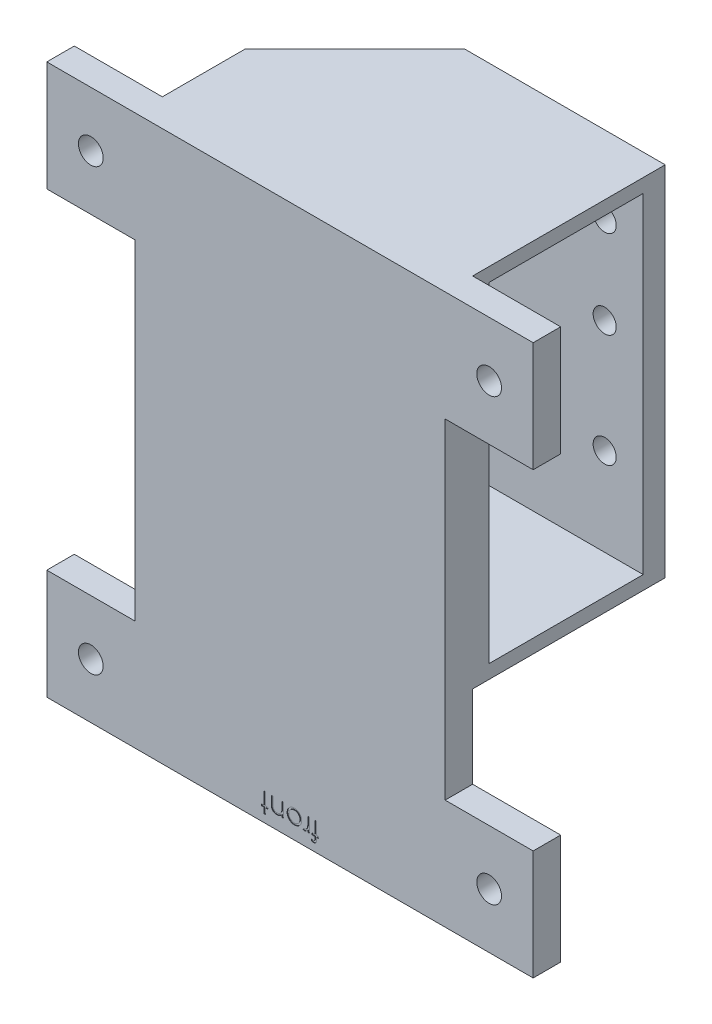
SolidWorks part; units mm, degrees
ref_plane "정면" through (0, 0, 0) normal (0, 0, 1) x (1, 0, 0)
ref_plane "윗면" through (0, 0, 0) normal (0, 1, 0) x (1, 0, 0)
ref_plane "우측면" through (0, 0, 0) normal (1, 0, 0) x (0, 0, -1)
sketch "스케치2" plane through (0, 0, 0) normal (0, 0, 1) x (1, 0, 0)
  line L1 (-28.2, 50) -> (28.2, 50)
  line L2 (-28.2, 50) -> (-28.2, -50)
  line L3 (-28.2, -50) -> (28.2, -50)
  line L4 (28.2, 50) -> (28.2, -50)
  line L5 (-28.2, 50) -> (28.2, -50) construction
  line L6 (-28.2, -50) -> (28.2, 50) construction
  point P0 (0, 0)
  dimension "D1" = 56.4
  dimension "D2" = 100
extrude "보스-돌출1" add sketch "스케치2" along normal blind 40
sketch "스케치3" plane through (0, 0, 40) normal (0, 0, 1) x (1, 0, 0)
  line L0 (-28.2, -45) -> (28.2, -45) construction
  line L1 (-28.2, 50) -> (-28.2, -50) construction
  line L2 (28.2, -50) -> (28.2, 50) construction
  line L4 (-28.2, -50) -> (28.2, -50) construction
  text T0 "front"
  dimension "D1" = 5
extrude "컷-돌출1" cut sketch "스케치3" against normal blind 0.1
sketch "스케치4" plane through (0, 0, 0) normal (0, 0, -1) x (-1, 0, 0)
  line L0 (-28.2, -50) -> (-28.2, 50) construction
  line L1 (-28.2, 50) -> (28.2, 50) construction
  circle A0 centre (-21.2, 40) radius 2.1
  circle A1 centre (-21.2, 24) radius 2.1
  circle A2 centre (-21.2, 3.5) radius 2.1
  dimension "D1" = 4.2
  dimension "D2" = 4.2
  dimension "D7" = 4.2
  dimension "D9" = 46.5
  dimension "D3" = 7
  dimension "D4" = 7
  dimension "D5" = 10
  dimension "D6" = 26
  dimension "D8" = 7
extrude "컷-돌출2" cut sketch "스케치4" against normal blind 20
sketch "스케치6" plane through (-28.2, 0, 0) normal (-1, 0, 0) x (0, 0, 1)
  line L1 (35, -50) -> (40, -50)
  line L2 (35, -50) -> (35, -30)
  line L3 (35, -30) -> (40, -30)
  line L4 (40, -50) -> (40, -30)
  line L5 (35, 50) -> (40, 50)
  line L6 (35, 50) -> (35, 30)
  line L7 (35, 30) -> (40, 30)
  line L8 (40, 50) -> (40, 30)
  dimension "D1" = 5
  dimension "D2" = 5
  dimension "D3" = 20
  dimension "D4" = 20
extrude "보스-돌출2" add sketch "스케치6" along normal blind 16
ref_plane "평면1" through (0, 0, 0) normal (-1, 0, 0) x (0, 0, 1)
mirror "대칭 복사1" about plane through (0, 0, 0) normal (-1, 0, 0) of "보스-돌출2"
hole_wizard "M4 여유 구멍1" positions "스케치8" profile "스케치9" hole size "M4" standard "KS" end condition through all
sketch "스케치8" plane through (0, 0, 40) normal (0, 0, 1) x (1, 0, 0)
  line L0 (-44.2, -50) -> (-44.2, -30) construction
  line L1 (-44.2, -30) -> (-28.2, -30) construction
  line L2 (-44.2, 30) -> (-28.2, 30) construction
  line L3 (-44.2, 30) -> (-44.2, 50) construction
  line L4 (44.2, 30) -> (44.2, 50) construction
  line L5 (44.2, 30) -> (28.2, 30) construction
  line L6 (44.2, -30) -> (28.2, -30) construction
  line L7 (44.2, -50) -> (44.2, -30) construction
  point P0 (-36.2, -40)
  point P2 (-36.2, 40)
  point P4 (36.2, 40)
  point P6 (36.2, -40)
  dimension "D1" = 8
  dimension "D2" = 10
  dimension "D3" = 10
  dimension "D4" = 8
  dimension "D5" = 8
  dimension "D6" = 10
  dimension "D7" = 10
  dimension "D8" = 8
sketch "스케치9" plane through (-36.2, -40, 40) normal (1, 0, 0) x (0, -1, 0)
  line L0 (0, 0) -> (0, 40)
  line L1 (0, 40) -> (2.25, 40)
  line L2 (2.25, 40) -> (2.25, 0)
  line L5 (2.25, 0) -> (0, 0)
  line L11 (0, -6.35) -> (0, 107.95) construction
  dimension "관통 구멍 지름" = 4.5
  dimension "관통 구멍 깊이" = 40
sketch "스케치10" plane through (-28.2, 0, 0) normal (-1, 0, 0) x (0, 0, 1)
  line L0 (35, -50) -> (0, -50)
  line L1 (0, -50) -> (0, -15)
  line L2 (0, 50) -> (0, -50) construction
  line L3 (0, -15) -> (35, -15)
  line L7 (35, -15) -> (35, -50)
  point P4 (35, -50)
  point P9 (35.3461, -50)
  dimension "D1" = 35
extrude "컷-돌출3" cut sketch "스케치10" against normal through all
chamfer "모따기3" distance 20 angle 45 1 edges at (-28.2, 17.5, 0)
sketch "스케치11" plane through (28.2, 0, 0) normal (1, 0, 0) x (0, 0, -1)
  line L0 (-35, 50) -> (0, 50) construction
  line L1 (-4, 47.5) -> (-32, 47.5)
  line L2 (-4, 47.5) -> (-4, -12.5)
  line L3 (-4, -12.5) -> (-32, -12.5)
  line L4 (-32, 47.5) -> (-32, -12.5)
  line L5 (0, -15) -> (0, 50) construction
  line L6 (-35, 50) -> (-35, 30) construction
  line L7 (-35, -15) -> (0, -15) construction
  dimension "D1" = 2.5
  dimension "D2" = 4
  dimension "D3" = 3
  dimension "D4" = 2.5
extrude "컷-돌출4" cut sketch "스케치11" against normal through all
